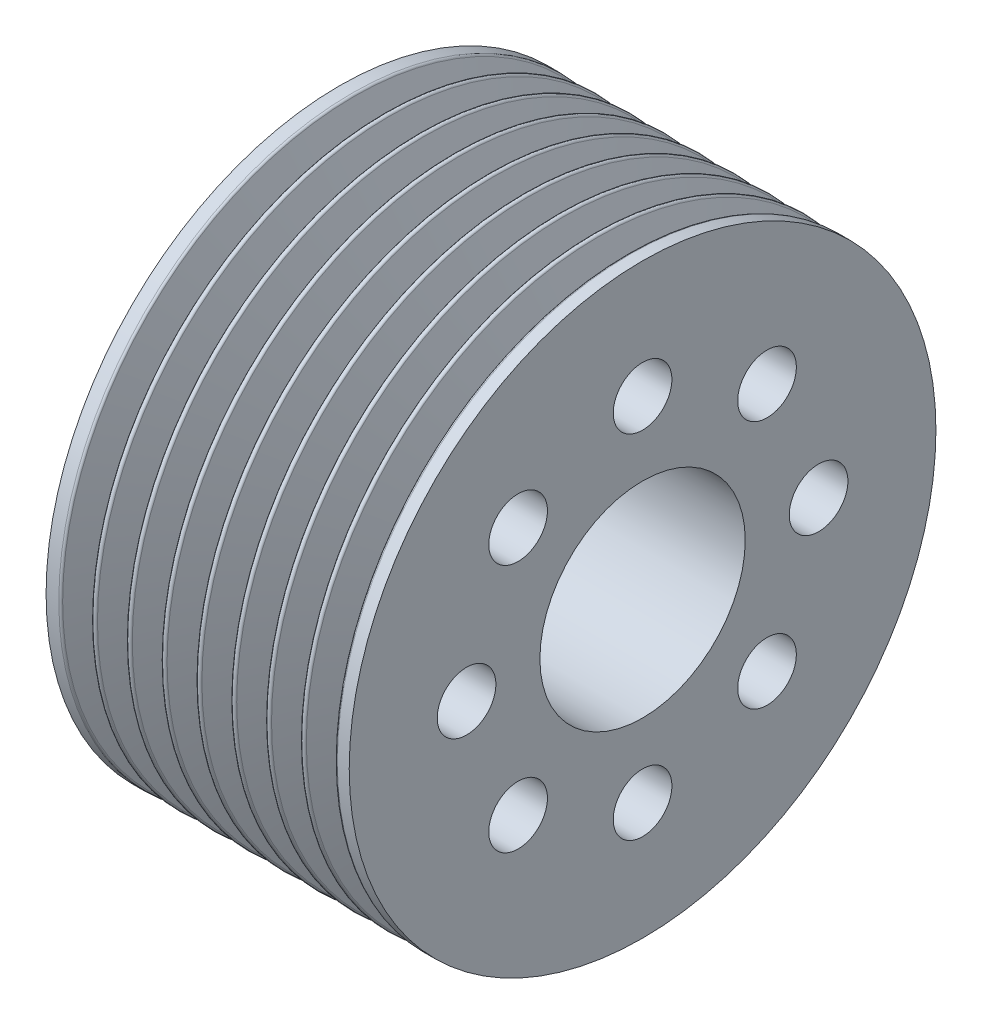
SolidWorks part; units mm, degrees
material "2018 Alloy"
ref_plane "Front Plane" through (0, 0, 0) normal (0, 0, 1) x (1, 0, 0)
ref_plane "Top Plane" through (0, 0, 0) normal (0, 1, 0) x (1, 0, 0)
ref_plane "Right Plane" through (0, 0, 0) normal (1, 0, 0) x (0, 0, -1)
sketch "Sketch1" plane through (0, 0, 0) normal (0, 0, 1) x (1, 0, 0)
  line L0 (49, 10.5) -> (49, 0) construction
  line L1 (49, 10.5) -> (49, 30)
  line L2 (49, 30) -> (18, 30)
  line L3 (18, 30) -> (18, 21.5)
  line L4 (49, 10.5) -> (31.5, 10.5)
  line L5 (0, 0) -> (49, 0) construction
  line L6 (18, 21.5) -> (31.5, 21.5)
  line L8 (0, 8.3175) -> (0, 0) construction
  line L9 (31.5, 10.5) -> (31.5, 21.5)
  dimension "D1" = 31
  dimension "D2" = 60
  dimension "D3" = 31.5
  dimension "D4" = 43
  dimension "D5" = 49
  dimension "D8" = 21
revolve "Revolve1" add sketch "Sketch1" angle 360 about L5
sketch "Sketch2" plane through (0, 0, 0) normal (0, 0, 1) x (1, 0, 0)
  line L0 (47.5458, 29.8376) -> (46.281, 26.4546)
  line L1 (45.719, 26.4546) -> (44.4542, 29.8376)
  line L2 (47.5458, 29.8376) -> (47.6066, 30) construction
  line L3 (49, 30) -> (18, 30) construction
  line L4 (44.4542, 29.8376) -> (44.3934, 30) construction
  line L5 (49, -30) -> (49, 30) construction
  line L6 (47.78, 30) -> (44.22, 30)
  line L7 (0, 0) -> (49, 0) construction
  arc A0 (47.5458, 29.8376) -> (47.78, 30) centre (47.78, 29.75) cw
  arc A1 (44.4542, 29.8376) -> (44.22, 30) centre (44.22, 29.75) ccw
  arc A2 (46.281, 26.4546) -> (45.719, 26.4546) centre (46, 26.5597) cw
  dimension "D2" = 0.25
  dimension "D3" = 0.3
  dimension "D1" = 41
  dimension "D4" = 3.56
  dimension "D5" = 3
revolve "Cut-Revolve1" cut sketch "Sketch2" angle 360 about L7
pattern_linear "LPattern1" count 8 spacing 3.56 along (-1, 0, 0) of "Cut-Revolve1"
sketch "Sketch3" plane through (49, 0, 0) normal (1, 0, 0) x (0, 0, -1)
  circle A0 centre (0, 0) radius 18 construction
  circle A1 centre (0, 18) radius 3
  circle A2 centre (12.7279, 12.7279) radius 3
  circle A3 centre (18, 0) radius 3
  circle A4 centre (12.7279, -12.7279) radius 3
  circle A5 centre (0, -18) radius 3
  circle A6 centre (-12.7279, -12.7279) radius 3
  circle A7 centre (-18, 0) radius 3
  circle A8 centre (-12.7279, 12.7279) radius 3
  dimension "D1" = 36
  dimension "D2" = 6
  dimension "D3" = 8
extrude "Cut-Extrude1" cut sketch "Sketch3" against normal up to surface (17.5 mm away) up to face at (31.5, 0, 10.5)
